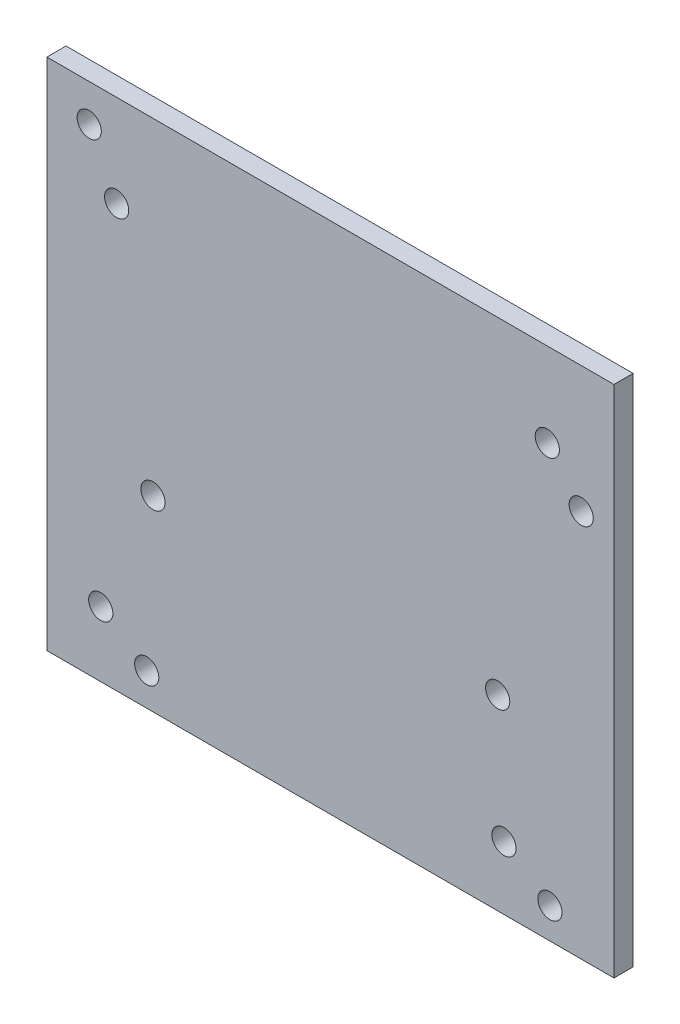
SolidWorks part; units mm, degrees
ref_plane "Front Plane" through (0, 0, 0) normal (0, 0, 1) x (1, 0, 0)
ref_plane "Top Plane" through (0, 0, 0) normal (0, 1, 0) x (1, 0, 0)
ref_plane "Right Plane" through (0, 0, 0) normal (1, 0, 0) x (0, 0, -1)
sketch "Sketch1" plane through (0, 0, 0) normal (0, 0, 1) x (1, 0, 0)
  line L0 (-563.2713, 236.4783) -> (-563.2713, 211.0783) construction
  line L5 (-563.2713, 211.0783) -> (-532.9383, 211.0783) construction
  line L6 (-532.9383, 211.0783) -> (-532.9383, 236.4783) construction
  line L7 (-532.9383, 236.4783) -> (-563.2713, 236.4783) construction
  line L8 (-522.9828, 355.6439) -> (-550.2429, 358.6271) construction
  line L9 (-550.2429, 358.6271) -> (-550.6427, 329.0949) construction
  line L10 (-550.6427, 329.0949) -> (-523.3826, 326.1117) construction
  line L11 (-523.3826, 326.1117) -> (-522.9828, 355.6439) construction
  line L12 (-670.9898, 372.1696) -> (-698.4132, 375.1707) construction
  line L13 (-698.4132, 375.1707) -> (-704.6618, 345.6213) construction
  line L14 (-704.6618, 345.6213) -> (-677.2384, 342.6203) construction
  line L15 (-677.2384, 342.6203) -> (-670.9898, 372.1696) construction
  line L16 (-667.7514, 211.0783) -> (-667.7514, 236.4783) construction
  line L17 (-667.7514, 236.4783) -> (-698.0844, 236.4783) construction
  line L18 (-698.0844, 236.4783) -> (-698.0844, 211.0783) construction
  line L19 (-698.0844, 211.0783) -> (-667.7514, 211.0783) construction
  line L20 (-563.2713, 236.4783) -> (-563.2713, 211.0783) construction
  line L21 (-563.2713, 211.0783) -> (-532.9383, 211.0783) construction
  line L22 (-532.9383, 211.0783) -> (-532.9383, 236.4783) construction
  line L23 (-532.9383, 236.4783) -> (-563.2713, 236.4783) construction
  line L24 (-522.9828, 355.6439) -> (-550.2429, 358.6271) construction
  line L25 (-550.2429, 358.6271) -> (-550.6427, 329.0949) construction
  line L26 (-550.6427, 329.0949) -> (-523.3826, 326.1117) construction
  line L27 (-523.3826, 326.1117) -> (-522.9828, 355.6439) construction
  line L28 (-670.9898, 372.1696) -> (-698.4132, 375.1707) construction
  line L29 (-698.4132, 375.1707) -> (-704.6618, 345.6213) construction
  line L30 (-704.6618, 345.6213) -> (-677.2384, 342.6203) construction
  line L31 (-677.2384, 342.6203) -> (-670.9898, 372.1696) construction
  line L32 (-667.7514, 211.0783) -> (-667.7514, 236.4783) construction
  line L33 (-667.7514, 236.4783) -> (-698.0844, 236.4783) construction
  line L34 (-698.0844, 236.4783) -> (-698.0844, 211.0783) construction
  line L35 (-698.0844, 211.0783) -> (-667.7514, 211.0783) construction
  line L36 (-698.4132, 375.1707) -> (-532.9383, 211.0783) construction
  line L37 (-698.0844, 211.0783) -> (-522.9828, 355.6439) construction
  line L39 (-707.8368, 207.9033) -> (-519.8078, 207.9033)
  line L40 (-707.8368, 207.9033) -> (-707.8368, 378.3457)
  line L41 (-707.8368, 378.3457) -> (-519.8078, 378.3457)
  line L42 (-519.8078, 207.9033) -> (-519.8078, 378.3457)
  line L43 (-707.8368, 207.9033) -> (-519.8078, 378.3457) construction
  line L44 (-707.8368, 378.3457) -> (-519.8078, 207.9033) construction
  circle A0 centre (-541.0463, 218.0633) radius 2.5273 construction
  circle A1 centre (-556.2863, 228.8583) radius 2.5273 construction
  circle A2 centre (-530.6695, 336.491) radius 2.5273 construction
  circle A3 centre (-541.9126, 350.4972) radius 2.5273 construction
  circle A4 centre (-684.7047, 347.8438) radius 2.5273 construction
  circle A5 centre (-693.8011, 366.0252) radius 2.5273 construction
  circle A6 centre (-689.9764, 229.4933) radius 2.5273 construction
  circle A7 centre (-674.7364, 218.6983) radius 2.5273 construction
  circle A8 centre (-541.0463, 218.0633) radius 2.5273 construction
  circle A9 centre (-556.2863, 228.8583) radius 2.5273 construction
  circle A10 centre (-530.6695, 336.491) radius 2.5273 construction
  circle A11 centre (-541.9126, 350.4972) radius 2.5273 construction
  circle A12 centre (-684.7047, 347.8438) radius 2.5273 construction
  circle A13 centre (-693.8011, 366.0252) radius 2.5273 construction
  circle A14 centre (-689.9764, 229.4933) radius 2.5273 construction
  circle A15 centre (-674.7364, 218.6983) radius 2.5273 construction
  circle A23 centre (-674.7364, 218.6983) radius 4.0127
  circle A24 centre (-689.9764, 229.4933) radius 4.0127
  circle A25 centre (-693.8011, 366.0252) radius 4.0127
  circle A26 centre (-684.7047, 347.8438) radius 4.0127
  circle A27 centre (-541.9126, 350.4972) radius 4.0127
  circle A28 centre (-530.6695, 336.491) radius 4.0127
  circle A29 centre (-541.0463, 218.0633) radius 4.0127
  circle A30 centre (-556.2863, 228.8583) radius 4.0127
  circle A31 centre (-558.3616, 269.9726) radius 3 construction
  circle A32 centre (-672.6612, 269.9726) radius 3 construction
  circle A33 centre (-558.3616, 269.9726) radius 3 construction
  circle A34 centre (-672.6612, 269.9726) radius 3 construction
  circle A35 centre (-558.3616, 269.9726) radius 4.0132
  circle A36 centre (-672.6612, 269.9726) radius 4.0132
  point P1 (-607.967, 285.4801)
  point P18 (-613.8223, 293.1245)
  dimension "D5" = 8.0254
  dimension "D6" = 8.0264
  dimension "D1" = 3.175
  dimension "D2" = 3.175
  dimension "D3" = 3.175
  dimension "D4" = 3.175
extrude "Boss-Extrude1" add sketch "Sketch1" along normal blind 6.35
